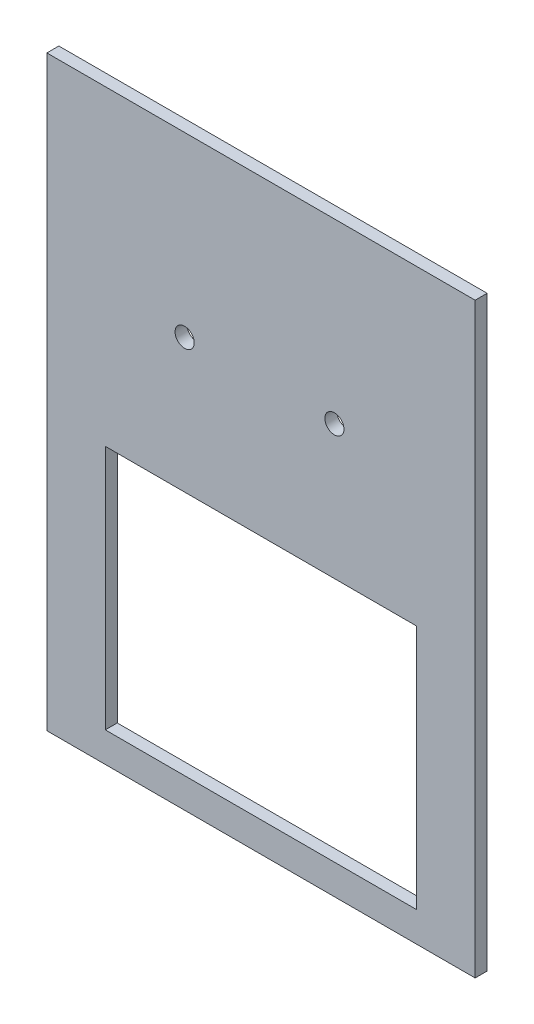
SolidWorks part; units mm, degrees
ref_plane "前视基准面" through (0, 0, 0) normal (0, 0, 1) x (1, 0, 0)
ref_plane "上视基准面" through (0, 0, 0) normal (0, 1, 0) x (1, 0, 0)
ref_plane "右视基准面" through (0, 0, 0) normal (1, 0, 0) x (0, 0, -1)
sketch "草图1" plane through (0, 0, 0) normal (0, 0, 1) x (1, 0, 0)
  line L0 (35.75, 47.5) -> (35.75, 50.5)
  line L2 (-35.75, 47.5) -> (-35.75, -47.5)
  line L3 (-35.75, -47.5) -> (35.75, -47.5)
  line L4 (35.75, 47.5) -> (35.75, -47.5)
  line L5 (-35.75, 47.5) -> (35.75, -47.5) construction
  line L6 (-35.75, -47.5) -> (35.75, 47.5) construction
  line L7 (-26, -1.5) -> (26, -1.5)
  line L8 (-26, -1.5) -> (-26, -42.5)
  line L9 (-26, -42.5) -> (26, -42.5)
  line L10 (26, -1.5) -> (26, -42.5)
  line L11 (-26, -1.5) -> (26, -42.5) construction
  line L12 (-26, -42.5) -> (26, -1.5) construction
  line L13 (35.75, 50.5) -> (-35.75, 50.5)
  line L14 (-35.75, 50.5) -> (-35.75, 47.5)
  point P0 (0, 0)
  point P5 (0, -22)
  dimension "D1" = 95
  dimension "D2" = 5
  dimension "D3" = 41
  dimension "D4" = 52
  dimension "D5" = 71.5
  dimension "D6" = 3
extrude "凸台-拉伸1" add sketch "草图1" along normal blind 2
hole_wizard "Ø3.0mm 暗销孔1" positions "草图2" profile "草图3" hole size "Ø3.0" standard "GB"
sketch "草图2" plane through (68.1593, -140.5, 0) normal (0, 0, -1) x (-1, 0, 0)
  point P0 (80.9071, 161.3794)
  point P3 (55.9071, 161.3794)
sketch "草图3" plane through (-12.7477, 20.8794, 0) normal (1, 0, 0) x (0, 1, 0)
  line L0 (0, 0) -> (0, 2.9614)
  line L1 (0, 2.9614) -> (1.6, 2)
  line L2 (1.6, 2) -> (1.6, 0)
  line L3 (1.6, 0) -> (0, 0)
  line L4 (0, 2.9614) -> (-1.6, 2) construction
  line L5 (0, -6.35) -> (0, 107.95) construction
  dimension "孔直径" = 3.2
  dimension "孔深度" = 2
  dimension "导头角度" = 118
